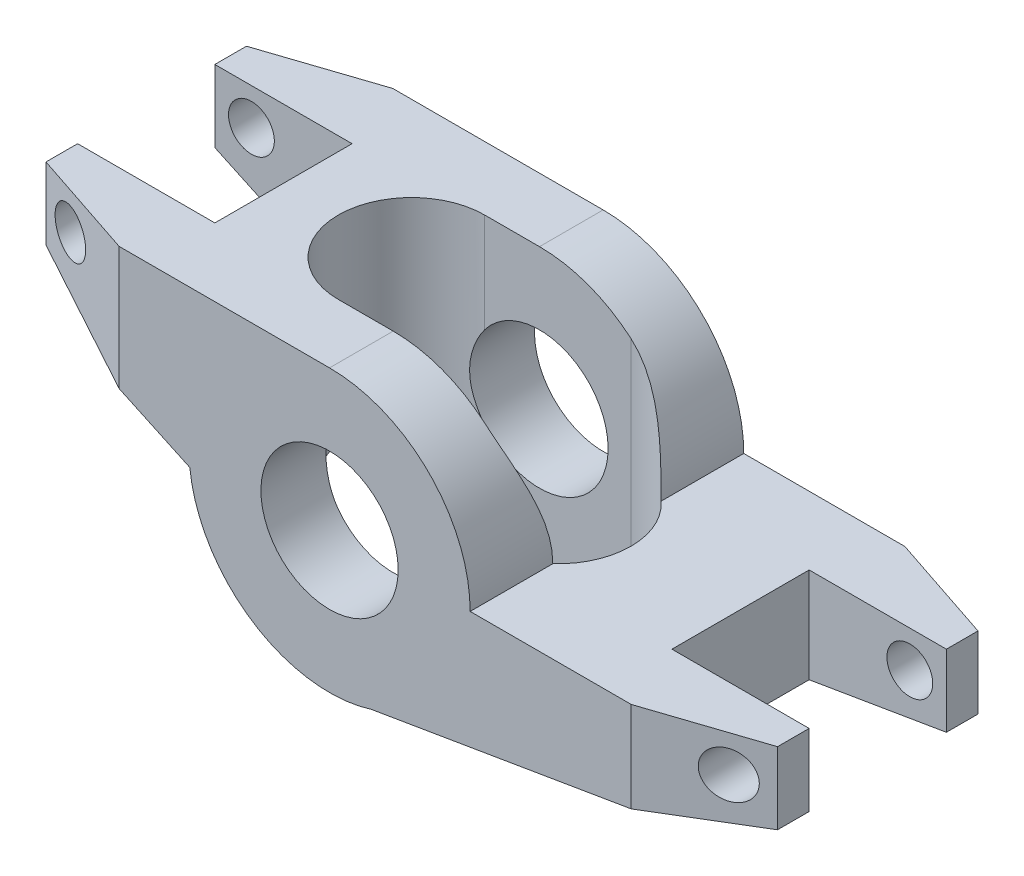
SolidWorks part; units mm, degrees
ref_plane "Front Plane" through (0, 0, 0) normal (0, 0, 1) x (1, 0, 0)
ref_plane "Top Plane" through (0, 0, 0) normal (0, 1, 0) x (1, 0, 0)
ref_plane "Right Plane" through (0, 0, 0) normal (1, 0, 0) x (0, 0, -1)
sketch "Sketch1" plane through (0, 0, 0) normal (0, 0, 1) x (1, 0, 0)
  line L0 (-243.4088, 0) -> (11927.0298, 0) construction
  line L1 (0, -243.4088) -> (0, 11927.0298) construction
  line L2 (0, 9.765) -> (-22.23, 9.765)
  line L3 (-22.23, 9.765) -> (-22.23, 4.765)
  line L4 (-22.23, 4.765) -> (-9.7056, -1.0752)
  line L5 (9.765, 0) -> (28.57, 0)
  line L6 (28.57, 0) -> (28.57, -5)
  line L7 (28.57, -5) -> (2.908, -9.3219)
  circle A0 centre (0, 0) radius 9.765
  circle A1 centre (0, 0) radius 4.765
  dimension "D1" = 19.53
  dimension "D2" = 9.53
  dimension "D3" = 22.23
  dimension "D4" = 5
  dimension "D5" = 25
  dimension "D6" = 28.57
extrude "Boss-Extrude1" add sketch "Sketch1" along normal mid plane 19 contours A0 L2 L3 L4 | A0 A1 | A0 L7 L6 L5
chamfer "Chamfer1" distance 2.54 distance2 7.62 1 edges at (-22.23, 7.265, 9.5)
chamfer "Chamfer2" distance 7.62 distance2 2.54 1 edges at (-22.23, 7.265, -9.5)
chamfer "Chamfer3" distance 7.62 distance2 2.54 1 edges at (28.57, -2.5, 9.5)
chamfer "Chamfer4" distance 2.54 distance2 7.62 1 edges at (28.57, -2.5, -9.5)
sketch "Sketch3" plane through (0, 0, 0) normal (0, 1, 0) x (1, 0, 0)
  line L0 (28.57, 6.96) -> (20.95, 9.5)
  line L1 (20.95, -9.5) -> (28.57, -6.96)
  line L2 (9.765, 9.5) -> (20.95, 9.5)
  line L3 (9.765, 9.5) -> (4.765, 9.5)
  line L4 (-4.765, 9.5) -> (-12.0114, 9.5)
  line L5 (9.765, -9.5) -> (20.95, -9.5)
  line L6 (9.765, -9.5) -> (4.765, -9.5)
  line L7 (-4.765, -9.5) -> (-12.0114, -9.5)
  line L8 (4.765, -9.5) -> (4.765, 9.5)
  line L9 (-4.765, 9.5) -> (-4.765, -9.5)
  line L10 (9.765, -9.5) -> (9.765, 9.5)
  line L11 (28.57, -6.96) -> (28.57, 6.96)
  line L12 (-12.0114, 9.5) -> (-12.0114, -9.5)
  line L13 (-12.0114, 9.5) -> (-12.0114, -9.5) construction
  line L14 (28.57, -6.96) -> (28.57, 6.96)
  line L15 (9.765, -9.5) -> (9.765, 9.5)
  line L16 (-4.765, 9.5) -> (-4.765, -9.5) construction
  line L17 (4.765, -9.5) -> (4.765, 9.5)
  line L18 (-4.765, -9.5) -> (-12.0114, -9.5) construction
  line L19 (9.765, -9.5) -> (4.765, -9.5)
  line L20 (9.765, -9.5) -> (20.95, -9.5)
  line L21 (-4.765, 9.5) -> (-12.0114, 9.5) construction
  line L22 (9.765, 9.5) -> (4.765, 9.5)
  line L23 (9.765, 9.5) -> (20.95, 9.5)
  line L24 (20.95, -9.5) -> (28.57, -6.96)
  line L25 (28.57, 6.96) -> (20.95, 9.5)
  line L26 (-3.81, 0) -> (6.35, 0) construction
  line L27 (-3.81, 5.08) -> (6.35, 5.08)
  line L28 (-3.81, -5.08) -> (6.35, -5.08)
  arc A0 (-3.81, 5.08) -> (-3.81, -5.08) centre (-3.81, 0) ccw
  arc A1 (6.35, -5.08) -> (6.35, 5.08) centre (6.35, 0) ccw
  point P15 (1.27, 0)
  dimension "D1" = 10.16
  dimension "D2" = 10.16
  dimension "D3" = 3.81
extrude "Cut-Extrude1" cut sketch "Sketch3" against normal through all both and the other way through all contours L27 A0 L28 L17 | L28 A1 L15 L27 L17 | L15 A1
sketch "Sketch4" plane through (0, 0, 0) normal (0, 1, 0) x (1, 0, 0)
  line L1 (-22.23, -4.765) -> (-12.7, -4.765)
  line L2 (-22.23, -4.765) -> (-22.23, 4.765)
  line L3 (-22.23, 4.765) -> (-12.7, 4.765)
  line L4 (-12.7, -4.765) -> (-12.7, 4.765)
  line L5 (28.57, -4.765) -> (19.04, -4.765)
  line L6 (28.57, -4.765) -> (28.57, 4.765)
  line L7 (9.765, -3.7609) -> (9.765, -9.5)
  line L8 (9.765, -9.5) -> (20.95, -9.5)
  line L9 (20.95, -9.5) -> (28.57, -6.96)
  line L10 (28.57, -6.96) -> (28.57, 6.96)
  line L11 (28.57, 6.96) -> (20.95, 9.5)
  line L12 (20.95, 9.5) -> (9.765, 9.5)
  line L13 (9.765, 9.5) -> (9.765, 3.7609)
  line L14 (9.765, -3.7609) -> (9.765, -9.5) construction
  line L15 (9.765, -9.5) -> (20.95, -9.5) construction
  line L16 (20.95, -9.5) -> (28.57, -6.96) construction
  line L17 (28.57, -6.96) -> (28.57, 6.96) construction
  line L18 (28.57, 6.96) -> (20.95, 9.5) construction
  line L19 (20.95, 9.5) -> (9.765, 9.5) construction
  line L20 (9.765, 9.5) -> (9.765, 3.7609) construction
  line L21 (28.57, 4.765) -> (19.04, 4.765)
  line L22 (19.04, -4.765) -> (19.04, 4.765)
  line L23 (-3.81, 5.08) -> (0, 5.08)
  line L24 (0, 5.08) -> (0, 9.5)
  line L25 (0, 9.5) -> (-14.61, 9.5)
  line L26 (-14.61, 9.5) -> (-22.23, 6.96)
  line L27 (-22.23, 6.96) -> (-22.23, -6.96)
  line L28 (-22.23, -6.96) -> (-14.61, -9.5)
  line L29 (-14.61, -9.5) -> (0, -9.5)
  line L30 (0, -9.5) -> (0, -5.08)
  line L31 (0, -5.08) -> (-3.81, -5.08)
  line L32 (-3.81, 5.08) -> (0, 5.08) construction
  line L33 (0, 5.08) -> (0, 9.5) construction
  line L34 (0, 9.5) -> (-14.61, 9.5) construction
  line L35 (-14.61, 9.5) -> (-22.23, 6.96) construction
  line L36 (-22.23, 6.96) -> (-22.23, -6.96) construction
  line L37 (-22.23, -6.96) -> (-14.61, -9.5) construction
  line L38 (-14.61, -9.5) -> (0, -9.5) construction
  line L39 (0, -9.5) -> (0, -5.08) construction
  line L40 (0, -5.08) -> (-3.81, -5.08) construction
  arc A1 (9.765, -3.7609) -> (9.765, 3.7609) centre (6.35, 0) ccw
  arc A2 (9.765, -3.7609) -> (9.765, 3.7609) centre (6.35, 0) ccw construction
  arc A3 (-3.81, 5.08) -> (-3.81, -5.08) centre (-3.81, 0) ccw
  arc A4 (-3.81, 5.08) -> (-3.81, -5.08) centre (-3.81, 0) ccw construction
  point P28 (-22.23, 0)
  point P29 (19.04, 0)
  point P33 (-17.465, 4.765)
  dimension "D3" = 9.53
  dimension "D4" = 9.53
  dimension "D1" = 0
  dimension "D2" = 0
extrude "Cut-Extrude2" cut sketch "Sketch4" against normal through all both and the other way through all
sketch "Sketch5" plane through (0, 0, 0) normal (0, 0, 1) x (1, 0, 0)
  line L0 (19.04, -6.605) -> (19.04, 0)
  line L1 (-12.7, 9.765) -> (-12.7, 0.3211)
  line L2 (-8.89, -4.0402) -> (-8.89, 9.765)
  line L3 (11.43, 0) -> (11.43, -7.8867)
  line L4 (11.43, 0) -> (19.04, 0)
  line L5 (-12.7, 0.3211) -> (-9.7056, -1.0752)
  line L6 (-8.89, 9.765) -> (-12.7, 9.765)
  line L7 (19.04, -6.605) -> (11.43, -7.8867)
  line L8 (19.04, -6.605) -> (11.43, -7.8867)
  line L9 (-8.89, 9.765) -> (-12.7, 9.765)
  line L10 (-12.7, 0.3211) -> (-9.7056, -1.0752)
  line L11 (11.43, 0) -> (19.04, 0)
  line L12 (11.43, 0) -> (11.43, -7.8867)
  line L13 (-8.89, -4.0402) -> (-8.89, 9.765)
  line L14 (-12.7, 9.765) -> (-12.7, 0.3211)
  line L15 (19.04, -6.605) -> (19.04, 0)
  line L16 (28.57, -5) -> (28.57, 0) construction
  line L17 (-22.23, 4.765) -> (-22.23, 9.765) construction
  line L18 (28.57, -5) -> (28.57, 0)
  line L19 (-22.23, 4.765) -> (-22.23, 9.765)
  line L20 (-12.7, 9.765) -> (-22.23, 9.765) construction
  line L21 (28.57, 0) -> (19.04, 0) construction
  arc A0 (-9.7056, -1.0752) -> (-8.89, -4.0402) centre (0, 0) ccw
  arc A1 (-9.7056, -1.0752) -> (-8.89, -4.0402) centre (0, 0) ccw
  circle A2 centre (-19.69, 7.225) radius 1.59
  circle A3 centre (26.03, -2.54) radius 1.59
  dimension "D1" = 3.18
  dimension "D2" = 3.18
  dimension "D3" = 2.54
  dimension "D4" = 2.54
  dimension "D5" = 2.54
  dimension "D6" = 2.54
extrude "Cut-Extrude3" cut sketch "Sketch5" against normal through all both and the other way through all contours A3 | A2
